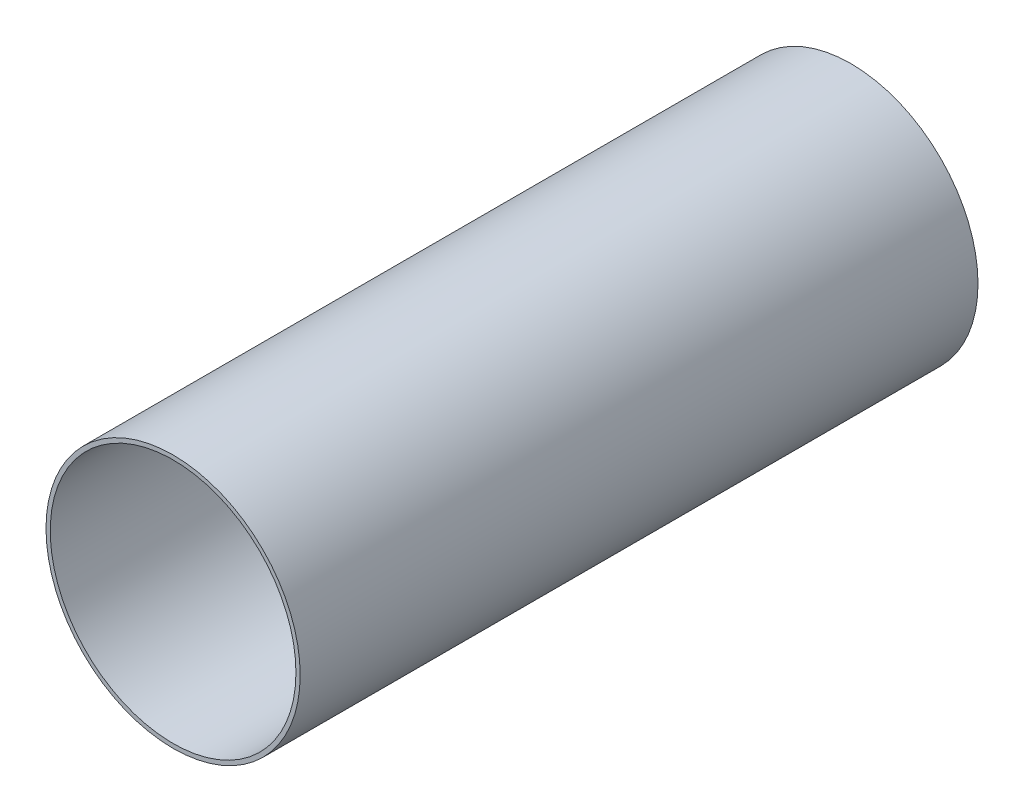
SolidWorks part; units mm, degrees
ref_plane "Front Plane" through (0, 0, 0) normal (0, 0, 1) x (1, 0, 0)
ref_plane "Top Plane" through (0, 0, 0) normal (0, 1, 0) x (1, 0, 0)
ref_plane "Right Plane" through (0, 0, 0) normal (1, 0, 0) x (0, 0, -1)
sketch "Sketch1" plane through (0, 0, 0) normal (0, 0, 1) x (1, 0, 0)
  circle A0 centre (0, 0) radius 30
  circle A1 centre (0, 0) radius 29
  dimension "D1" = 60
  dimension "D2" = 1
extrude "Boss-Extrude1" add sketch "Sketch1" along normal blind 160
